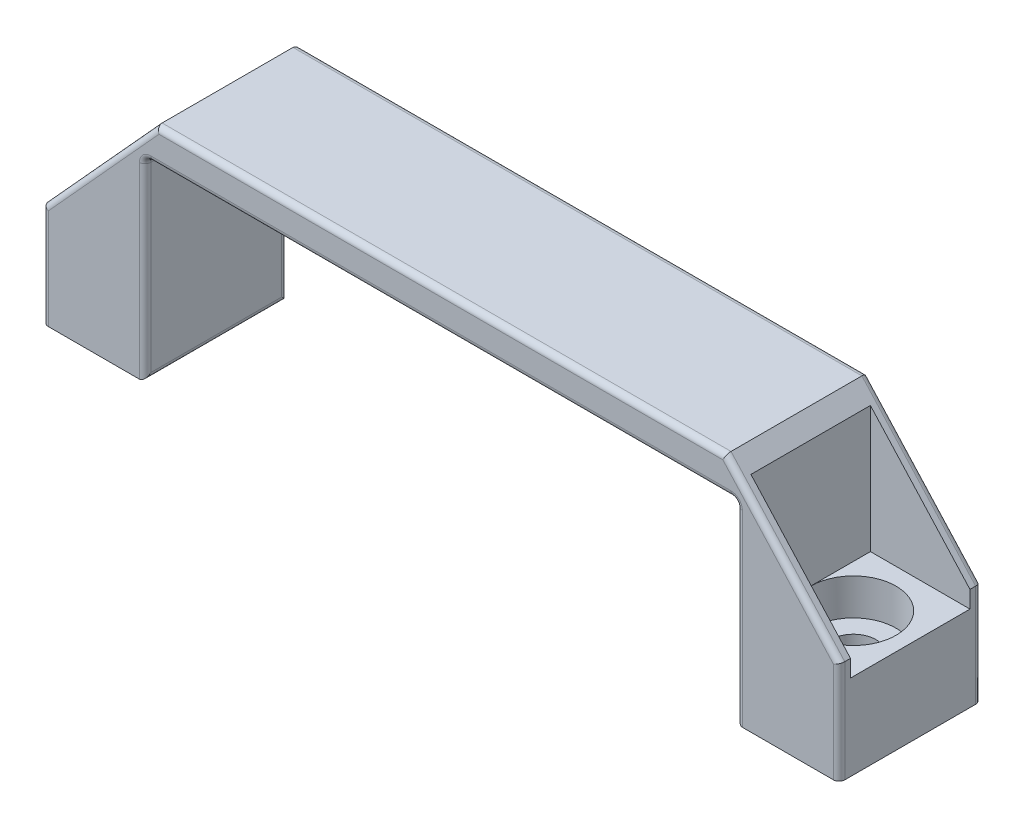
SolidWorks part; units mm, degrees
material "Q235A焊接件"
ref_plane "前视" through (0, 0, 0) normal (0, 0, 1) x (1, 0, 0)
ref_plane "上视" through (0, 0, 0) normal (0, 1, 0) x (1, 0, 0)
ref_plane "右视" through (0, 0, 0) normal (1, 0, 0) x (0, 0, -1)
sketch "草图1" plane through (0, 0, 0) normal (0, 1, 0) x (1, 0, 0)
  line L1 (70, -12.5) -> (-70, -12.5)
  line L2 (70, -12.5) -> (70, 12.5)
  line L3 (70, 12.5) -> (-70, 12.5)
  line L4 (-70, -12.5) -> (-70, 12.5)
  line L5 (70, -12.5) -> (-70, 12.5) construction
  line L6 (70, 12.5) -> (-70, -12.5) construction
  point P0 (0, 0)
  dimension "D1" = 140
  dimension "D2" = 25
extrude "凸台-拉伸1" add sketch "草图1" along normal blind 40
sketch "草图2" plane through (0, 0, 12.5) normal (0, 0, 1) x (1, 0, 0)
  line L0 (50, 0) -> (-50, 0) construction
  line L1 (-52, 0) -> (52, 0)
  line L2 (-52, 0) -> (-52, 34)
  line L3 (-52, 34) -> (52, 34)
  line L4 (52, 0) -> (52, 34)
  line L5 (-70, 40) -> (70, 40) construction
  line L6 (-70, 40) -> (-70, 0) construction
  line L7 (70, 40) -> (70, 0) construction
  line L8 (-70, 40) -> (-50, 40)
  line L9 (-50, 40) -> (-70, 18)
  line L10 (-70, 18) -> (-70, 40)
  line L11 (70, 40) -> (50, 40)
  line L12 (50, 40) -> (70, 18)
  line L13 (70, 18) -> (70, 40)
  dimension "D1" = 6
  dimension "D2" = 18
  dimension "D3" = 18
  dimension "D4" = 100
  dimension "D5" = 18
extrude "切除-拉伸1" cut sketch "草图2" against normal through all
sketch "草图3" plane through (0, 40, 0) normal (0, 1, 0) x (1, 0, 0)
  line L0 (-70, 12.5) -> (-70, -12.5) construction
  line L1 (-70, 10.5) -> (-52.5, 10.5)
  line L2 (-70, 10.5) -> (-70, -10.5)
  line L3 (-70, -10.5) -> (-52.5, -10.5)
  line L4 (-52.5, 10.5) -> (-52.5, -10.5)
  line L5 (70, 12.5) -> (70, -12.5) construction
  line L6 (70, 10.5) -> (52.5, 10.5)
  line L7 (70, 10.5) -> (70, -10.5)
  line L8 (70, -10.5) -> (52.5, -10.5)
  line L9 (52.5, 10.5) -> (52.5, -10.5)
  line L10 (-70, 12.5) -> (-50, 12.5) construction
  line L11 (-70, -12.5) -> (-50, -12.5) construction
  dimension "D1" = 2
  dimension "D2" = 2
  dimension "D3" = 105
extrude "切除-拉伸2" cut sketch "草图3" against normal blind 25
hole_wizard "M6 六角凹头螺钉的柱形沉头孔1" positions "草图5" profile "草图4" counterbore size "M6" standard "ISO" end condition through all
sketch "草图5" plane through (0, 15, 0) normal (0, 1, 0) x (-1, 0, 0)
  line L0 (0, 12.5) -> (0, -12.5) construction
  line L1 (50, 12.5) -> (-50, 12.5) construction
  line L2 (0, 50) -> (0, -50) construction
  line L3 (0, 0) -> (60, 0) construction
  line L4 (-50, -12.5) -> (50, -12.5) construction
  point P0 (60, 0)
  point P16 (-60, 0)
  dimension "D1" = 120
  dimension "D2" = 60
sketch "草图4" plane through (-60, 15, 0) normal (1, 0, 0) x (0, 0, 1)
  line L0 (0, 0) -> (0, 15)
  line L1 (0, 15) -> (4, 15)
  line L3 (4, 15) -> (4, 6.4)
  line L4 (4, 6.4) -> (7.5, 6.4)
  line L5 (7.5, 6.4) -> (7.5, 0)
  line L7 (7.5, 0) -> (0, 0)
  line L11 (0, -6.35) -> (0, 107.95) construction
  dimension "通孔孔直径" = 8
  dimension "通孔孔深度" = 15
  dimension "柱形沉头孔直径" = 15
  dimension "柱形沉头孔深度" = 6.4
fillet "圆角1" radius 1 10 edges at (-52, 17, -12.5) (-52, 0, 0) (-52, 17, 12.5) (0, 34, -12.5) (-52, 34, 0) (0, 34, 12.5) (52, 0, 0) (52, 17, -12.5) (52, 34, 0) (52, 17, 12.5)
fillet "圆角2" radius 1 10 edges at (-70, 9, -12.5) (-60, 29, -12.5) (0, 40, -12.5) (70, 9, -12.5) (60, 29, -12.5) (-70, 9, 12.5) (-60, 29, 12.5) (0, 40, 12.5) (60, 29, 12.5) (70, 9, 12.5)
